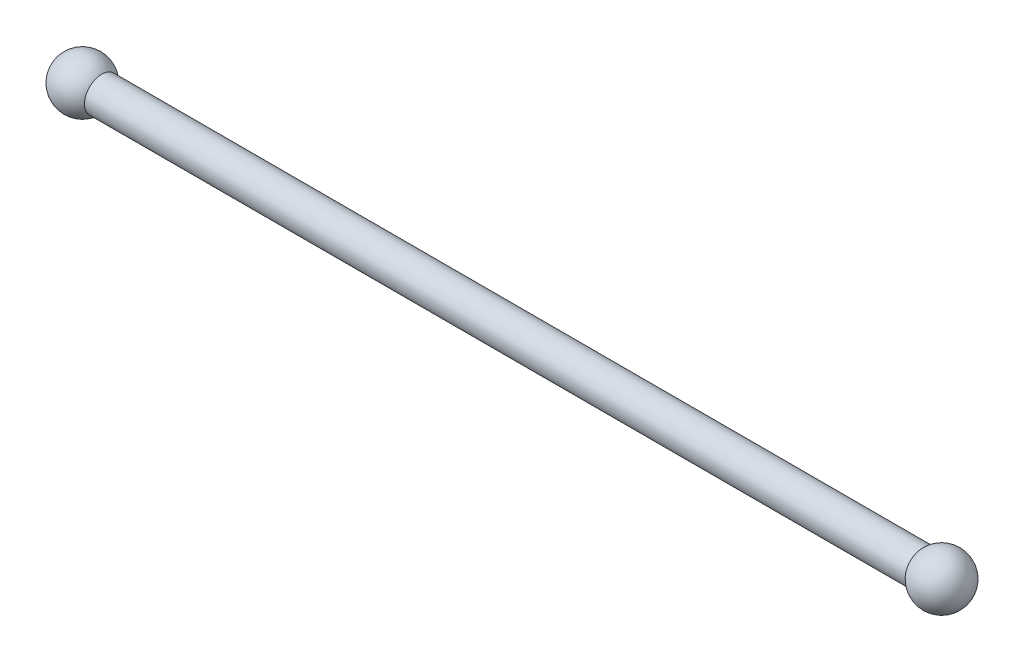
SolidWorks part; units mm, degrees
ref_plane "Płaszczyzna przednia" through (0, 0, 0) normal (0, 0, 1) x (1, 0, 0)
ref_plane "Płaszczyzna górna" through (0, 0, 0) normal (0, 1, 0) x (1, 0, 0)
ref_plane "Płaszczyzna prawa" through (0, 0, 0) normal (1, 0, 0) x (0, 0, -1)
sketch "Szkic1" plane through (0, 0, 0) normal (0, 0, 1) x (1, 0, 0)
  line L1 (0, 0) -> (125, 0)
  line L2 (0, 0) -> (0, 5)
  line L3 (0, 5) -> (125, 5)
  line L4 (125, 0) -> (125, 5)
  dimension "D1" = 5
  dimension "D2" = 125
revolve "Obrót1" add sketch "Szkic1" angle 360 about L1
sketch "Szkic2" plane through (125, 0, 0) normal (1, 0, 0) x (0, 0, -1)
  line L0 (-7.5, 0) -> (7.5, 0)
  arc A0 (7.5, 0) -> (-7.5, 0) centre (0, 0) ccw
  dimension "D1" = 15
revolve "Obrót3" add sketch "Szkic2" angle 360 about L0
mirror "Lustro1" about plane through (0, 0, 0) normal (1, 0, 0) of "Obrót1", "Obrót3"
